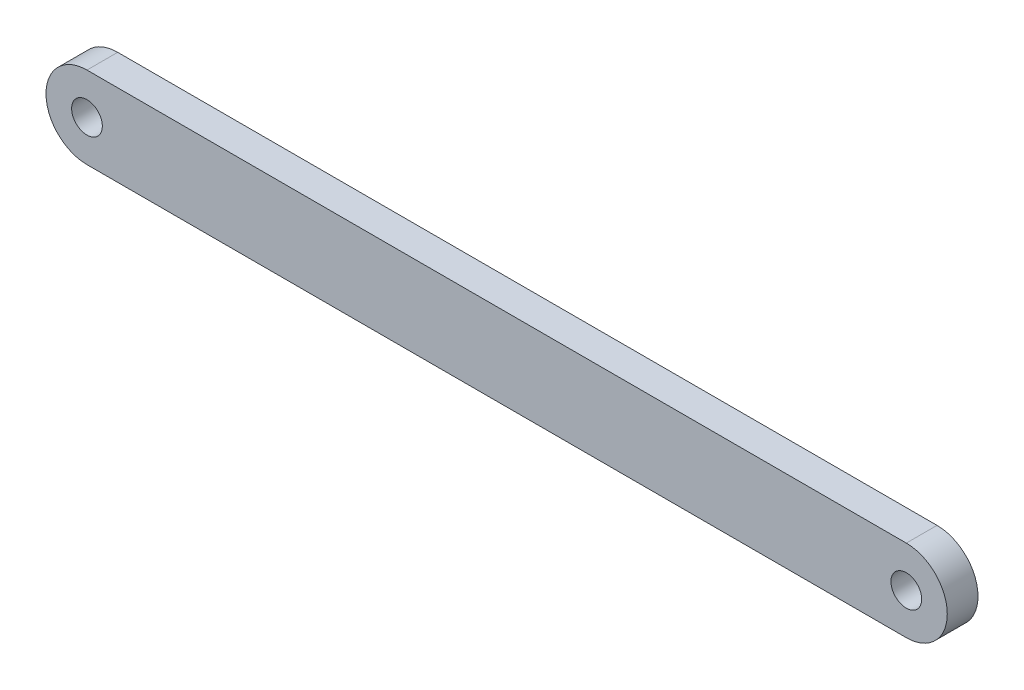
SolidWorks part; units mm, degrees
ref_plane "Plan de face" through (0, 0, 0) normal (0, 0, 1) x (1, 0, 0)
ref_plane "Plan de dessus" through (0, 0, 0) normal (0, 1, 0) x (1, 0, 0)
ref_plane "Plan de droite" through (0, 0, 0) normal (1, 0, 0) x (0, 0, -1)
sketch "Esquisse7" plane through (0, 0, 0) normal (0, 0, 1) x (1, 0, 0)
  line L0 (-65.045, -11.5842) -> (14.955, -11.5842) construction
  line L1 (-65.045, -7.5842) -> (14.955, -7.5842)
  line L2 (-65.045, -15.5842) -> (14.955, -15.5842)
  circle A0 centre (-65.045, -11.5842) radius 1.5
  circle A1 centre (14.955, -11.5842) radius 1.5
  arc A2 (-65.045, -7.5842) -> (-65.045, -15.5842) centre (-65.045, -11.5842) ccw
  arc A3 (14.955, -15.5842) -> (14.955, -7.5842) centre (14.955, -11.5842) ccw
  point P4 (-25.045, -11.5842)
  dimension "D1" = 3
  dimension "D2" = 3
  dimension "D3" = 4
  dimension "D4" = 80
extrude "Boss.-Extru.7" add sketch "Esquisse7" along normal blind 3 separate body
